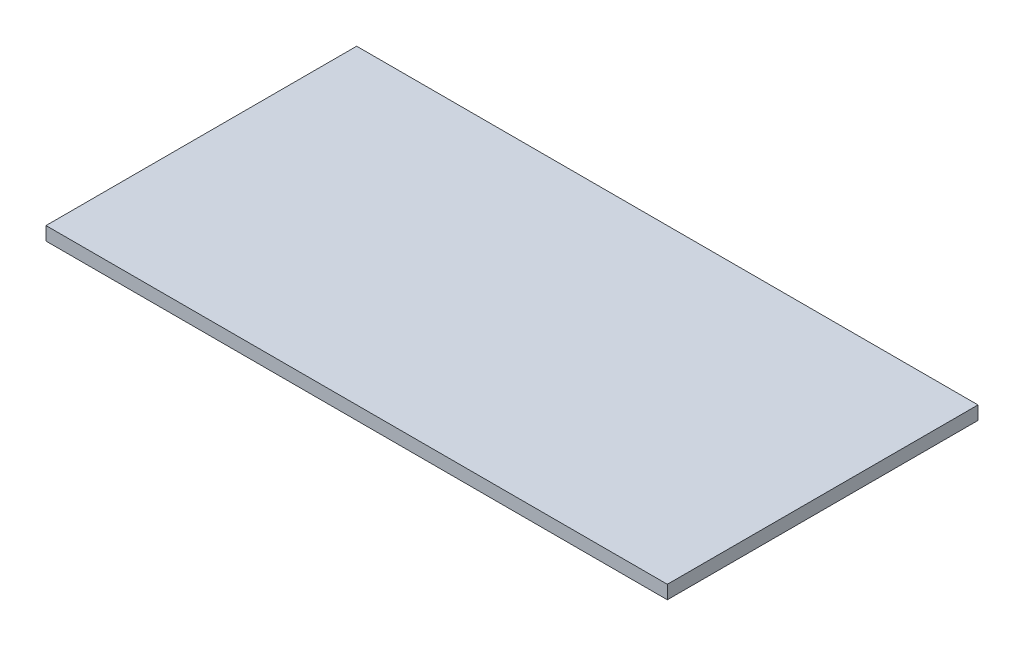
SolidWorks part; units mm, degrees
ref_plane "Front Plane" through (0, 0, 0) normal (0, 0, 1) x (1, 0, 0)
ref_plane "Top Plane" through (0, 0, 0) normal (0, 1, 0) x (1, 0, 0)
ref_plane "Right Plane" through (0, 0, 0) normal (1, 0, 0) x (0, 0, -1)
sketch "Sketch1" plane through (0, 0, 0) normal (0, 1, 0) x (1, 0, 0)
  line L1 (76.2, -38.1) -> (-76.2, -38.1)
  line L2 (76.2, -38.1) -> (76.2, 38.1)
  line L3 (76.2, 38.1) -> (-76.2, 38.1)
  line L4 (-76.2, -38.1) -> (-76.2, 38.1)
  line L5 (76.2, -38.1) -> (-76.2, 38.1) construction
  line L6 (76.2, 38.1) -> (-76.2, -38.1) construction
  point P0 (0, 0)
  dimension "D1" = 152.4
  dimension "D2" = 76.2
extrude "Boss-Extrude1" add sketch "Sketch1" along normal blind 3.302
equation "\"thick\"= 0.125in"
equation "\"D2@Sketch1\"=3"
